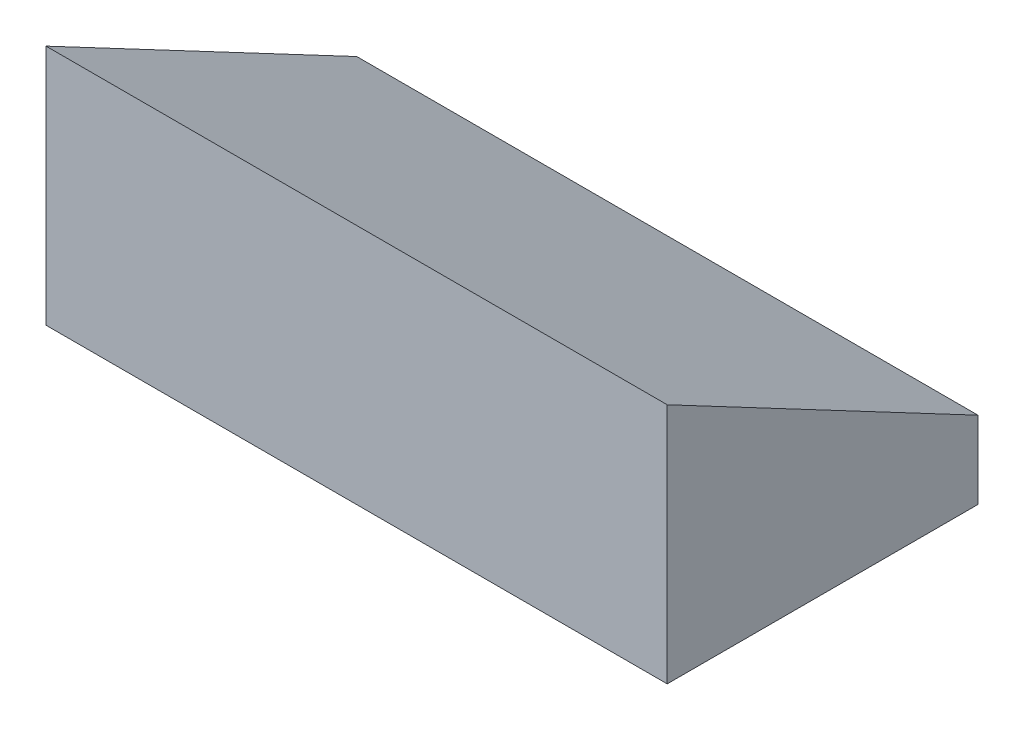
SolidWorks part; units mm, degrees
ref_plane "Front Plane" through (0, 0, 0) normal (0, 0, 1) x (1, 0, 0)
ref_plane "Top Plane" through (0, 0, 0) normal (0, 1, 0) x (1, 0, 0)
ref_plane "Right Plane" through (0, 0, 0) normal (1, 0, 0) x (0, 0, -1)
sketch "Sketch1" plane through (0, 0, 0) normal (1, 0, 0) x (0, 0, -1)
  line L0 (0, 0) -> (0, 6.16)
  line L1 (0, 0) -> (7.92, 0)
  line L3 (7.92, 0) -> (7.92, 1.97)
  line L4 (7.92, 1.97) -> (0, 6.16)
  dimension "D1" = 6.16
  dimension "D2" = 7.92
  dimension "D3" = 1.97
extrude "Boss-Extrude1" add sketch "Sketch1" along normal blind 15.83
shell "Shell1" thickness 1.5
sketch "Sketch2" plane through (0, 0, 0) normal (0, 1, 0) x (1, 0, 0)
  line L1 (15.83, 0) -> (0, 0) construction
  line L3 (15.83, 0) -> (15.83, 7.92) construction
  circle A0 centre (7.915, 3.96) radius 1.5
  circle A1 centre (7.915, 3.96) radius 0.67
  dimension "D2" = 7.915
  dimension "D3" = 3
  dimension "D4" = 1.34
  dimension "D1" = 3.96
extrude "Boss-Extrude3" add sketch "Sketch2" along normal up to surface (3.1616 mm away)
